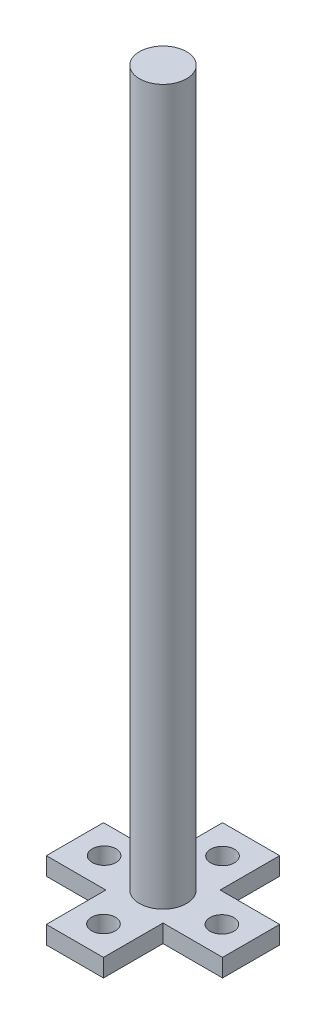
SolidWorks part; units mm, degrees
ref_plane "前视基准面" through (0, 0, 0) normal (0, 0, 1) x (1, 0, 0)
ref_plane "上视基准面" through (0, 0, 0) normal (0, 1, 0) x (1, 0, 0)
ref_plane "右视基准面" through (0, 0, 0) normal (1, 0, 0) x (0, 0, -1)
other "Configuration Table"
sketch "草图1" plane through (0, 0, 0) normal (0, 1, 0) x (1, 0, 0)
  line L0 (-14.9378, 4.9391) -> (35717.0744, -34969.6704) construction
  line L5 (-15, -5) -> (15, 5) construction
  line L6 (-15, 5) -> (15, -5) construction
  line L11 (-5, -15) -> (5, 15) construction
  line L12 (-5, 15) -> (5, -15) construction
  line L13 (-5, 5) -> (-35360.3391, -35350.3391) construction
  line L14 (5, 5) -> (35360.3391, -35350.3391) construction
  line L15 (5, -5) -> (-35350.3391, -35360.3391) construction
  line L16 (-4.8, 14.8) -> (4.8, 14.8)
  line L17 (4.8, -14.8) -> (4.8, 14.8)
  line L18 (-4.8, -14.8) -> (4.8, -14.8)
  line L19 (-4.8, -14.8) -> (-4.8, 14.8)
  line L20 (-14.8, 4.8) -> (14.8, 4.8)
  line L21 (14.8, -4.8) -> (14.8, 4.8)
  line L22 (-14.8, -4.8) -> (14.8, -4.8)
  line L23 (-14.8, -4.8) -> (-14.8, 4.8)
  circle A0 centre (0, 0) radius 4
  circle A1 centre (-9.9464, 0.0536) radius 2
  circle A2 centre (0.0536, 9.9464) radius 2
  circle A3 centre (9.9464, -0.0536) radius 2
  circle A4 centre (-0.0536, -9.9464) radius 2
  point P0 (0, 0)
  point P6 (0, 0)
  dimension "D5" = 8
  dimension "D6" = 4
  dimension "D1" = 30
  dimension "D2" = 30
  dimension "D3" = 10
  dimension "D4" = 10
  dimension "D7" = 4
extrude "凸台-拉伸2" add sketch "草图1" along normal blind 3 contours L23 L22 L19 L20 A1 | L22 L19 L18 L17 A4 | L19 L22 L17 L20 A0 | L17 L22 L21 L20 A3 | L19 L20 L17 L16 A2 | A0
sketch "草图2" plane through (0, 3, 0) normal (0, 1, 0) x (1, 0, 0)
  circle A0 centre (0, 0) radius 3.95
  dimension "D1" = 7.9
extrude "凸台-拉伸3" add sketch "草图2" along normal blind 120
